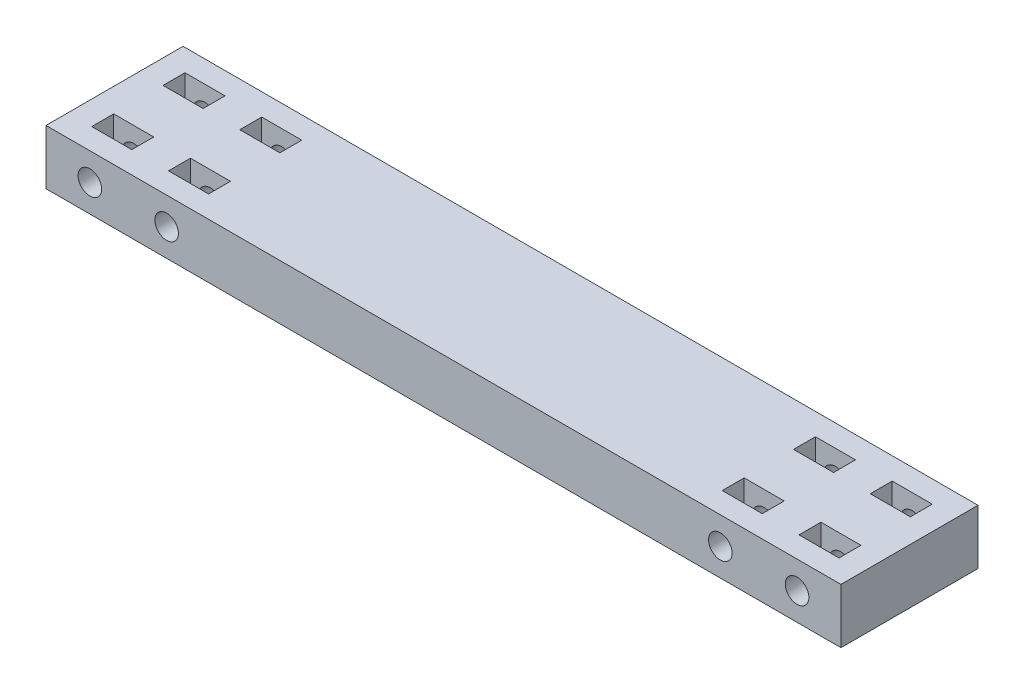
SolidWorks part; units mm, degrees
ref_plane "Front Plane" through (0, 0, 0) normal (0, 0, 1) x (1, 0, 0)
ref_plane "Top Plane" through (0, 0, 0) normal (0, 1, 0) x (1, 0, 0)
ref_plane "Right Plane" through (0, 0, 0) normal (1, 0, 0) x (0, 0, -1)
sketch "Sketch1" plane through (0, 0, 0) normal (0, 1, 0) x (1, 0, 0)
  line L7 (0, 0) -> (145, 0)
  line L8 (0, 0) -> (0, 25)
  line L9 (0, 25) -> (145, 25)
  line L10 (145, 0) -> (145, 25)
  dimension "D1" = 25
  dimension "D3" = 145
extrude "Boss-Extrude1" add sketch "Sketch1" along normal blind 10
sketch "Sketch2" plane through (0, 0, 0) normal (0, 0, 1) x (1, 0, 0)
  line L0 (0, 5) -> (145, 5) construction
  line L1 (0, 10) -> (0, 0) construction
  line L2 (145, 10) -> (145, 0) construction
  line L3 (72.5, 10) -> (72.5, 0) construction
  line L4 (0, 10) -> (145, 10) construction
  line L5 (0, 0) -> (145, 0) construction
  circle A0 centre (8, 5) radius 2.15
  circle A1 centre (137, 5) radius 2.15
  circle A2 centre (22, 5) radius 2.15
  circle A3 centre (123, 5) radius 2.15
  circle A4 centre (137, 5) radius 2.15
  dimension "D1" = 4.3
  dimension "D2" = 8
  dimension "D4" = 14
  dimension "D3" = 2
extrude "Cut-Extrude1" cut sketch "Sketch2" against normal through all contours A2 | A0 | A3 | A1
sketch "Sketch3" plane through (0, 10, 0) normal (0, 1, 0) x (1, 0, 0)
  line L0 (145, 12.5) -> (0, 12.5) construction
  line L1 (145, 0) -> (145, 25) construction
  line L2 (0, 0) -> (0, 25) construction
  line L3 (72.5, 0) -> (72.5, 25) construction
  line L4 (0, 0) -> (145, 0) construction
  line L5 (0, 25) -> (145, 25) construction
  line L6 (137, 0) -> (137, 25) construction
  line L7 (140.65, 21) -> (133.35, 21)
  line L8 (140.65, 8) -> (133.35, 8)
  line L9 (140.65, 8) -> (140.65, 4)
  line L10 (140.65, 4) -> (133.35, 4)
  line L11 (133.35, 8) -> (133.35, 4)
  line L12 (140.65, 8) -> (133.35, 4) construction
  line L13 (140.65, 4) -> (133.35, 8) construction
  line L14 (133.35, 17) -> (133.35, 21)
  line L15 (140.65, 17) -> (133.35, 17)
  line L16 (140.65, 17) -> (140.65, 21)
  line L17 (126.65, 8) -> (126.65, 4)
  line L18 (126.65, 8) -> (119.35, 8)
  line L19 (119.35, 8) -> (119.35, 4)
  line L20 (126.65, 4) -> (119.35, 4)
  line L21 (126.65, 21) -> (119.35, 21)
  line L22 (119.35, 17) -> (119.35, 21)
  line L23 (126.65, 17) -> (119.35, 17)
  line L24 (126.65, 17) -> (126.65, 21)
  line L25 (4.35, 4) -> (11.65, 8) construction
  line L26 (4.35, 8) -> (11.65, 4) construction
  line L27 (8, 0) -> (8, 25) construction
  line L28 (18.35, 17) -> (18.35, 21)
  line L29 (18.35, 17) -> (25.65, 17)
  line L30 (25.65, 17) -> (25.65, 21)
  line L31 (18.35, 21) -> (25.65, 21)
  line L32 (18.35, 4) -> (25.65, 4)
  line L33 (25.65, 8) -> (25.65, 4)
  line L34 (18.35, 8) -> (25.65, 8)
  line L35 (18.35, 8) -> (18.35, 4)
  line L36 (4.35, 17) -> (4.35, 21)
  line L37 (4.35, 17) -> (11.65, 17)
  line L38 (11.65, 17) -> (11.65, 21)
  line L39 (11.65, 8) -> (11.65, 4)
  line L40 (4.35, 4) -> (11.65, 4)
  line L41 (4.35, 8) -> (4.35, 4)
  line L42 (4.35, 8) -> (11.65, 8)
  line L43 (4.35, 21) -> (11.65, 21)
  point P14 (137, 6)
  point P49 (8, 6)
  dimension "D1" = 8
  dimension "D2" = 7.3
  dimension "D3" = 6.5
  dimension "D4" = 4
  dimension "D6" = 14
  dimension "D5" = 2
extrude "Cut-Extrude2" cut sketch "Sketch3" against normal up to next
